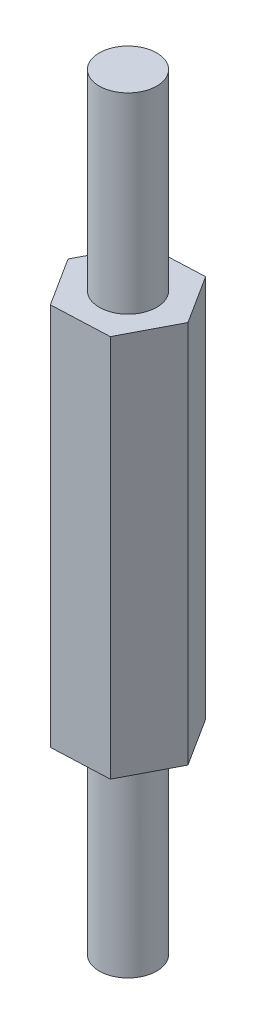
SolidWorks part; units mm, degrees
ref_plane "Front Plane" through (0, 0, 0) normal (0, 0, 1) x (1, 0, 0)
ref_plane "Top Plane" through (0, 0, 0) normal (0, 1, 0) x (1, 0, 0)
ref_plane "Right Plane" through (0, 0, 0) normal (1, 0, 0) x (0, 0, -1)
sketch "Sketch3" plane through (0, 0, 0) normal (0, 1, 0) x (1, 0, 0)
  line L1 (1.389, 2.6622) -> (-1.611, 2.534)
  line L2 (-1.611, 2.534) -> (-3, -0.1282)
  line L3 (-3, -0.1282) -> (-1.389, -2.6622)
  line L4 (-1.389, -2.6622) -> (1.611, -2.534)
  line L5 (1.611, -2.534) -> (3, 0.1282)
  line L6 (3, 0.1282) -> (1.389, 2.6622)
  circle A0 centre (0, 0) radius 2.6004 construction
  dimension "D2" = 5.2009
  dimension "D1" = 6
extrude "Boss-Extrude1" add sketch "Sketch3" along normal blind 20
sketch "Sketch4" plane through (0, 20, 0) normal (0, 1, 0) x (1, 0, 0)
  circle A0 centre (0, 0) radius 1.5
  dimension "D1" = 3
extrude "Boss-Extrude2" add sketch "Sketch4" along normal blind 10
sketch "Sketch5" plane through (0, 0, 0) normal (0, -1, 0) x (1, 0, 0)
  circle A0 centre (0, 0) radius 1.5
  dimension "D1" = 3
extrude "Boss-Extrude3" add sketch "Sketch5" along normal blind 10
